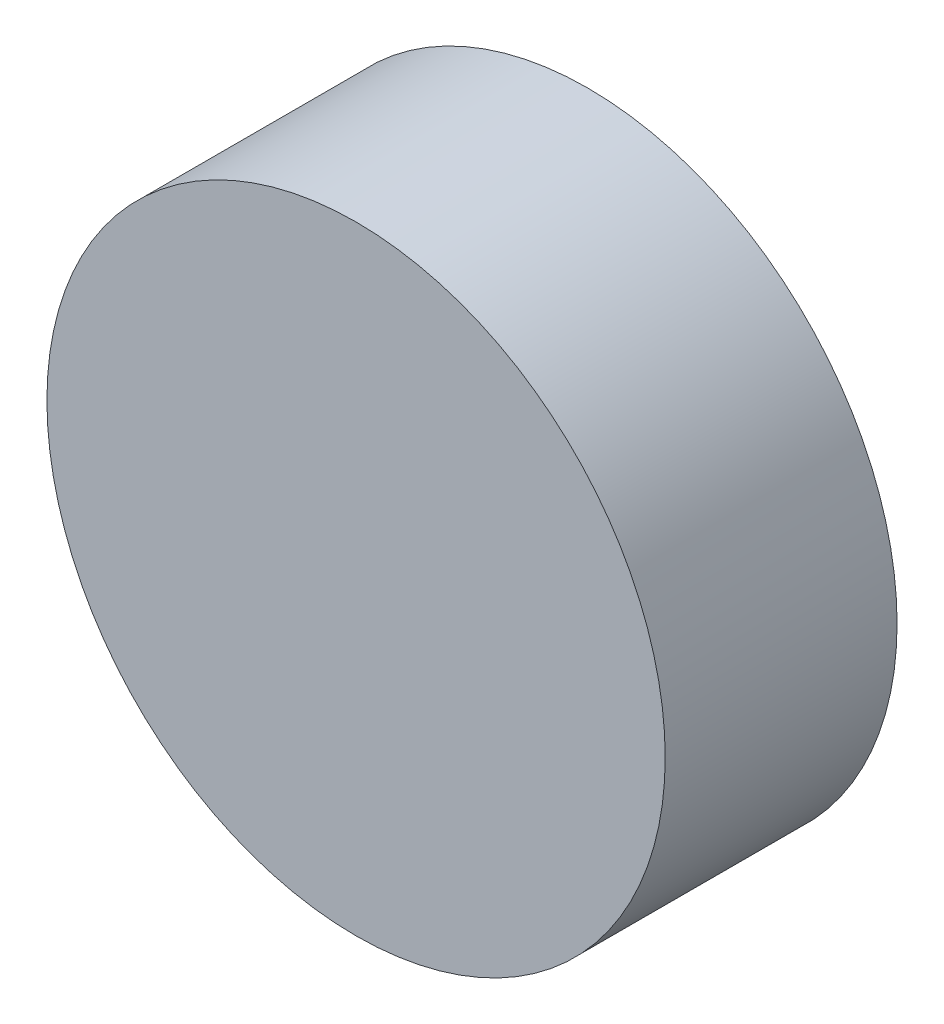
SolidWorks part; units mm, degrees
ref_plane "Płaszczyzna przednia" through (0, 0, 0) normal (0, 0, 1) x (1, 0, 0)
ref_plane "Płaszczyzna górna" through (0, 0, 0) normal (0, 1, 0) x (1, 0, 0)
ref_plane "Płaszczyzna prawa" through (0, 0, 0) normal (1, 0, 0) x (0, 0, -1)
sketch "Szkic1" plane through (0, 0, 0) normal (0, 0, 1) x (1, 0, 0)
  circle A0 centre (0, 0) radius 14
  dimension "D1" = 28
extrude "Dodanie-wyciągnięcie1" add sketch "Szkic1" along normal blind 10.5
